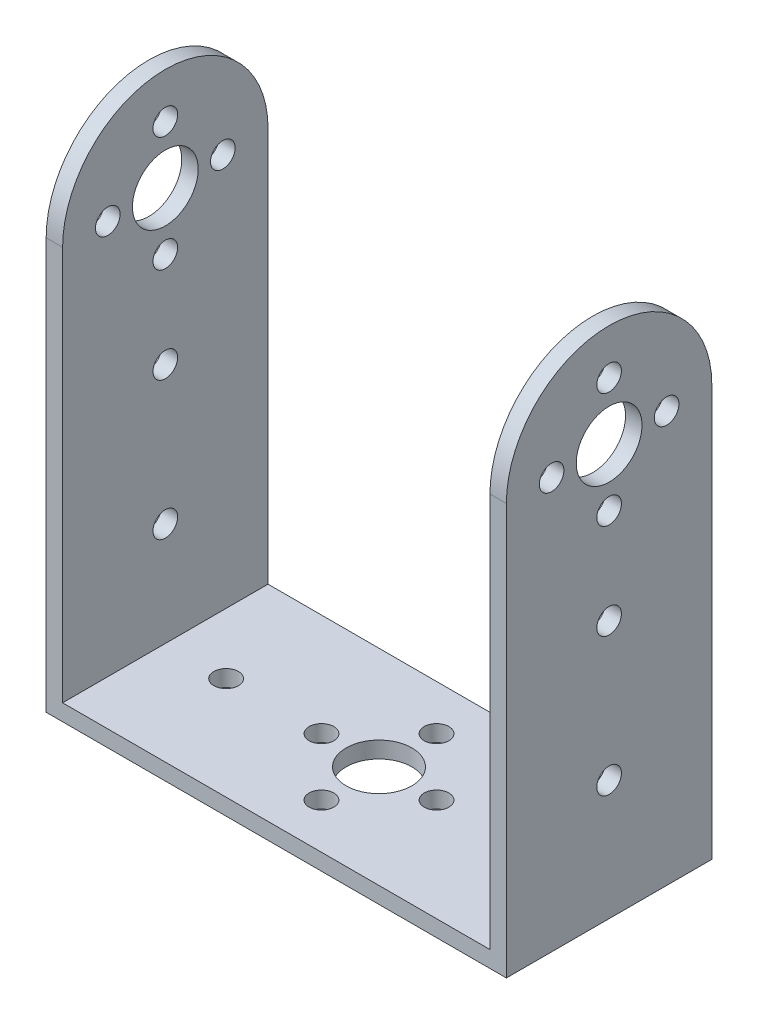
SolidWorks part; units mm, degrees
ref_plane "前视基准面" through (0, 0, 0) normal (0, 0, 1) x (1, 0, 0)
ref_plane "上视基准面" through (0, 0, 0) normal (0, 1, 0) x (1, 0, 0)
ref_plane "右视基准面" through (0, 0, 0) normal (1, 0, 0) x (0, 0, -1)
other "Configuration Table"
sketch "草图2" plane through (0, 0, 0) normal (0, 0, 1) x (1, 0, 0)
  line L0 (0, 0) -> (-26, 0)
  line L1 (-26, 0) -> (-26, 62.5)
  line L2 (-26, 62.5) -> (-28, 62.5)
  line L3 (-28, 62.5) -> (-28, -2)
  line L4 (-28, -2) -> (28, -2)
  line L5 (28, -2) -> (28, 62.5)
  line L6 (28, 62.5) -> (26, 62.5)
  line L7 (26, 62.5) -> (26, 0)
  line L8 (26, 0) -> (0, 0)
  dimension "D1" = 2
  dimension "D2" = 2
  dimension "D3" = 2
  dimension "D4" = 26
  dimension "D5" = 62.5
extrude "凸台-拉伸1" add sketch "草图2" along normal blind 25
sketch "草图3" plane through (0, 0, 0) normal (0, 1, 0) x (1, 0, 0)
  line L0 (0, -55) -> (0, 55) construction
  line L1 (0, -12.5) -> (26, -12.5) construction
  line L2 (26, -25) -> (26, 0) construction
  circle A0 centre (0, -12.5) radius 4
  circle A1 centre (0, -5.5) radius 1.5
  circle A2 centre (-18.6, -12.5) radius 1.5
  circle A3 centre (18.6, -12.5) radius 1.5
  circle A4 centre (7, -12.5) radius 1.5
  circle A5 centre (0, -19.5) radius 1.5
  circle A6 centre (-7, -12.5) radius 1.5
  point P4 (0, 0)
  point P19 (0, -12.5)
  dimension "D1" = 3
  dimension "D2" = 8
  dimension "D3" = 7
  dimension "D4" = 3
  dimension "D6" = 18.6
  dimension "D5" = 4
extrude "切除-拉伸1" cut sketch "草图3" against normal through all
sketch "草图4" plane through (28, 0, 0) normal (1, 0, 0) x (0, 0, -1)
  line L0 (-12.5, 48) -> (-12.5, 62.5) construction
  line L1 (-25, 62.5) -> (0, 62.5) construction
  line L2 (-25, -2) -> (0, -2) construction
  line L3 (-25, -2) -> (-25, 62.5) construction
  line L4 (0, -2) -> (0, 62.5) construction
  line L5 (0, 48) -> (0, 62.5)
  line L6 (-25, 62.5) -> (0, 62.5)
  line L7 (-25, 48) -> (-25, 62.5)
  circle A0 centre (-12.5, 48) radius 4
  circle A1 centre (-12.5, 55) radius 1.5
  circle A2 centre (-5.5, 48) radius 1.5
  circle A3 centre (-12.5, 41) radius 1.5
  circle A4 centre (-19.5, 48) radius 1.5
  circle A5 centre (-12.5, 29.4) radius 1.5
  circle A6 centre (-12.5, 12.6) radius 1.5
  arc A7 (-25, 48) -> (0, 48) centre (-12.5, 48) cw
  point P10 (0, 0)
  point P16 (-12.5, 48)
  point P17 (0, 0)
  dimension "D1" = 8
  dimension "D2" = 3
  dimension "D5" = 3
  dimension "D6" = 3
  dimension "D7" = 16.8
  dimension "D10" = 14.5
  dimension "D3" = 7
  dimension "D8" = 18.6
  dimension "D9" = 50
  dimension "D4" = 4
extrude "切除-拉伸2" cut sketch "草图4" against normal through all
